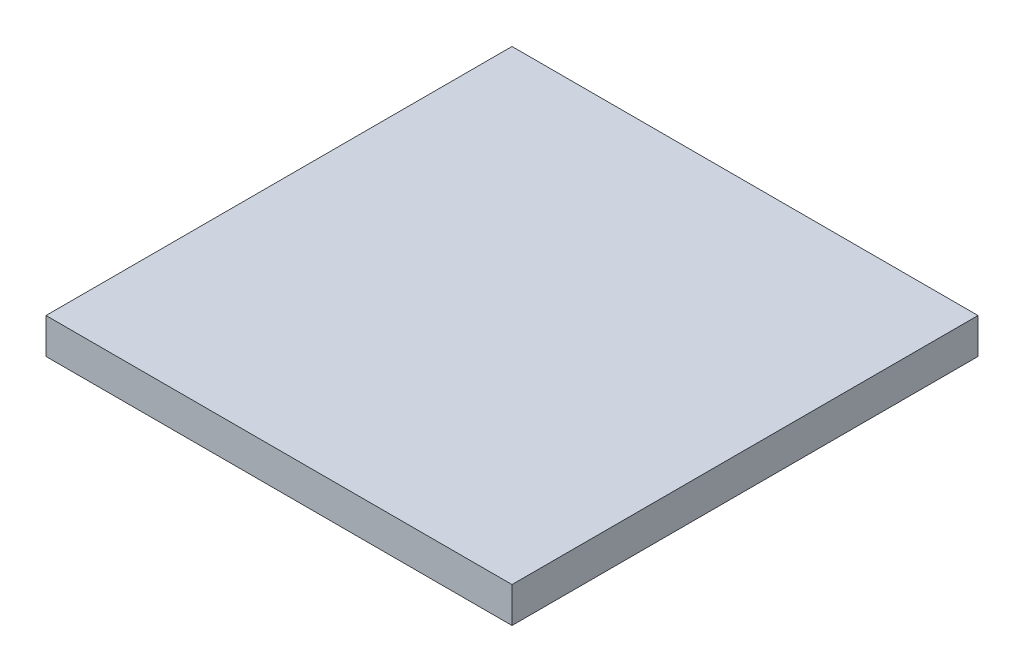
SolidWorks part; units mm, degrees
material "Epoxy, renforcé"
ref_plane "Plan de face" through (0, 0, 0) normal (0, 0, 1) x (1, 0, 0)
ref_plane "Plan de dessus" through (0, 0, 0) normal (0, 1, 0) x (1, 0, 0)
ref_plane "Plan de droite" through (0, 0, 0) normal (1, 0, 0) x (0, 0, -1)
sketch "Esquisse1" plane through (0, 0, 0) normal (0, 1, 0) x (1, 0, 0)
  line L1 (10.5, 10.5) -> (-10.5, 10.5)
  line L2 (10.5, 10.5) -> (10.5, -10.5)
  line L3 (10.5, -10.5) -> (-10.5, -10.5)
  line L4 (-10.5, 10.5) -> (-10.5, -10.5)
  line L5 (10.5, 10.5) -> (-10.5, -10.5) construction
  line L6 (10.5, -10.5) -> (-10.5, 10.5) construction
  point P0 (0, 0)
  dimension "D1" = 21
extrude "Boss.-Extru.1" add sketch "Esquisse1" along normal blind 1.6
